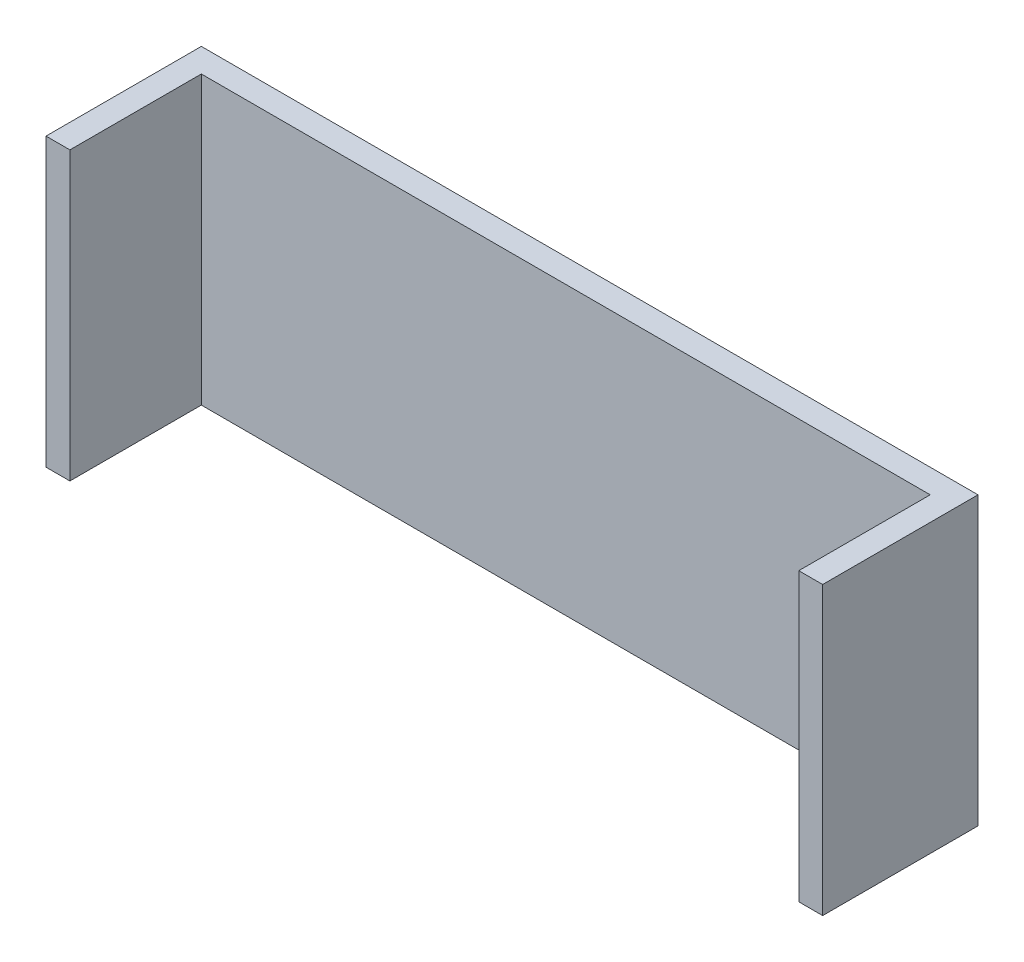
SolidWorks part; units mm, degrees
ref_plane "前基準面" through (0, 0, 0) normal (0, 0, 1) x (1, 0, 0)
ref_plane "上基準面" through (0, 0, 0) normal (0, 1, 0) x (1, 0, 0)
ref_plane "右基準面" through (0, 0, 0) normal (1, 0, 0) x (0, 0, -1)
sketch "草圖1" plane through (0, 0, 0) normal (0, 0, 1) x (1, 0, 0)
  line L1 (0, 0) -> (-65, 0)
  line L2 (0, 0) -> (0, 24)
  line L3 (0, 24) -> (-65, 24)
  line L4 (-65, 0) -> (-65, 24)
  dimension "D1" = 65
  dimension "D2" = 24
extrude "填料-伸長1" add sketch "草圖1" along normal blind 13
sketch "草圖2" plane through (0, 0, 13) normal (0, 0, 1) x (1, 0, 0)
  line L0 (-65, 0) -> (0, 0) construction
  line L1 (-63, 24) -> (-2, 24)
  line L2 (-63, 24) -> (-63, 0)
  line L3 (-63, 0) -> (-2, 0)
  line L4 (-2, 24) -> (-2, 0)
  line L5 (-65, 24) -> (-65, 0) construction
  dimension "D1" = 24
  dimension "D2" = 0
  dimension "D3" = 61
  dimension "D4" = 2
extrude "除料-伸長1" cut sketch "草圖2" against normal blind 11
